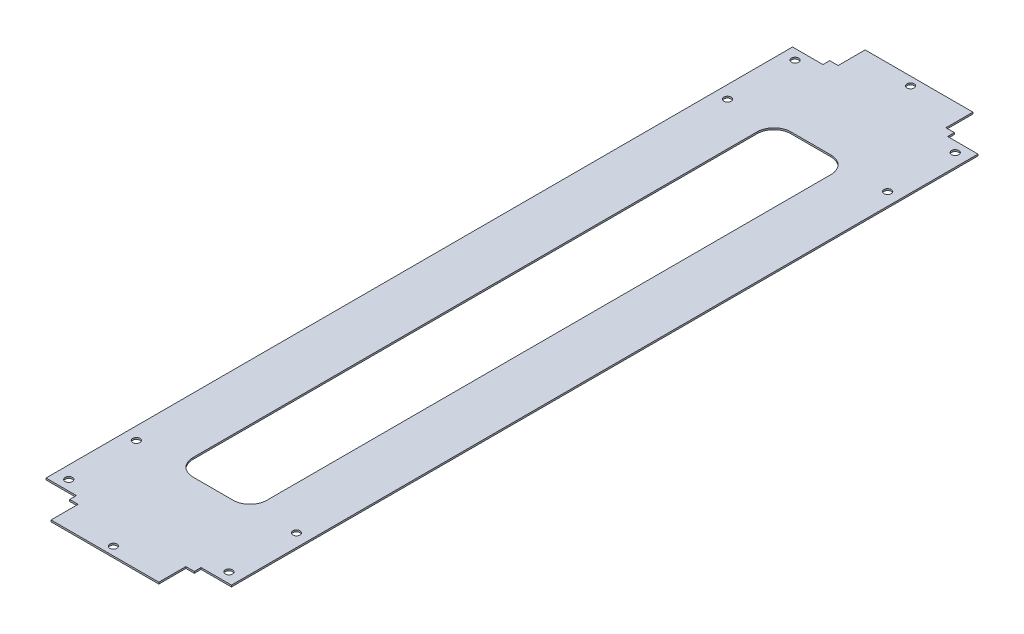
SolidWorks part; units mm, degrees
ref_plane "Front Plane" through (0, 0, 0) normal (0, 0, 1) x (1, 0, 0)
ref_plane "Top Plane" through (0, 0, 0) normal (0, 1, 0) x (1, 0, 0)
ref_plane "Right Plane" through (0, 0, 0) normal (1, 0, 0) x (0, 0, -1)
sketch "Sketch1" plane through (0, 0, 0) normal (0, 1, 0) x (1, 0, 0)
  line L0 (0, 0) -> (0, 221) construction
  line L1 (-54.9, -221) -> (-36.9, -221)
  line L3 (-36.9, 221) -> (-54.9, 221)
  line L4 (-54.9, 221) -> (-54.9, -221)
  line L16 (36.9, -221) -> (54.9, -221)
  line L17 (54.9, -221) -> (54.9, 221)
  line L25 (54.9, 221) -> (36.9, 221)
  line L26 (36.9, 221) -> (36.9, -221) construction
  line L27 (-21.9, 0) -> (0, 0) construction
  line L28 (-36.9, 221) -> (-36.9, 225)
  line L31 (-36.9, -221) -> (36.9, -221) construction
  line L32 (-36.9, 225) -> (-31.9, 225)
  line L33 (-31.9, 225) -> (-31.9, 241)
  line L35 (-36.9, 221) -> (36.9, 221) construction
  line L37 (-36.9, -221) -> (-36.9, 221) construction
  line L38 (0, 0) -> (21.9, 0) construction
  line L39 (-31.9, 241) -> (31.9, 241)
  line L40 (31.9, 241) -> (31.9, 225)
  line L41 (-21.9, 0) -> (-54.9, 0) construction
  line L42 (-21.9, 177) -> (21.9, 177)
  line L43 (-21.9, 177) -> (-21.9, -177)
  line L44 (-21.9, -177) -> (21.9, -177)
  line L45 (21.9, 177) -> (21.9, -177)
  line L46 (-21.9, 177) -> (21.9, -177) construction
  line L47 (-21.9, -177) -> (21.9, 177) construction
  line L48 (47.4, -175) -> (-47.4, -175) construction
  line L49 (47.4, -175) -> (47.4, 175) construction
  line L50 (47.4, 175) -> (-47.4, 175) construction
  line L51 (-47.4, -175) -> (-47.4, 175) construction
  line L52 (47.4, -175) -> (-47.4, 175) construction
  line L53 (47.4, 175) -> (-47.4, -175) construction
  line L54 (47.4, 215) -> (-47.4, 215) construction
  line L55 (47.4, 215) -> (47.4, -215) construction
  line L56 (47.4, -215) -> (-47.4, -215) construction
  line L57 (-47.4, 215) -> (-47.4, -215) construction
  line L58 (47.4, 215) -> (-47.4, -215) construction
  line L59 (47.4, -215) -> (-47.4, 215) construction
  line L60 (21.9, 0) -> (54.9, 0) construction
  line L61 (31.9, 225) -> (36.9, 225)
  line L62 (36.9, 225) -> (36.9, 221)
  line L63 (-31.9, 225) -> (31.9, 225) construction
  line L64 (0, 221) -> (0, 225) construction
  line L65 (-36.9, -221) -> (-36.9, -225)
  line L66 (-36.9, -225) -> (-31.9, -225)
  line L67 (-31.9, -225) -> (-31.9, -241)
  line L68 (-31.9, -241) -> (31.9, -241)
  line L69 (31.9, -241) -> (31.9, -225)
  line L70 (31.9, -225) -> (36.9, -225)
  line L71 (36.9, -225) -> (36.9, -221)
  line L72 (-31.9, -225) -> (31.9, -225) construction
  line L73 (0, -241) -> (0, -236) construction
  line L74 (0, 225) -> (0, 236) construction
  line L75 (0, 236) -> (0, 241) construction
  line L76 (0, -236) -> (0, -225) construction
  line L77 (0, -225) -> (0, -221) construction
  line L78 (0, -221) -> (0, 0) construction
  circle A2 centre (-47.4, 175) radius 2.15
  circle A3 centre (47.4, 175) radius 2.15
  circle A4 centre (-47.4, -175) radius 2.15
  circle A5 centre (47.4, -175) radius 2.15
  circle A6 centre (-47.4, -215) radius 2.15
  circle A7 centre (47.4, -215) radius 2.15
  circle A8 centre (47.4, 215) radius 2.15
  circle A9 centre (-47.4, 215) radius 2.15
  circle A10 centre (0, 236) radius 2.15
  circle A11 centre (0, -236) radius 2.15
  point P0 (0, 0)
  point P37 (0, 0)
  point P40 (0, 0)
  dimension "D12" = 4.3
  dimension "D5" = 40
  dimension "D15" = 94.8
  dimension "D3" = 10.5
  dimension "D14" = 10.5
  dimension "D4" = 18
  dimension "D16" = 18
  dimension "D18" = 4
  dimension "D11" = 38
  dimension "D7" = 10
  dimension "D6" = 21
  dimension "D9" = 4
  dimension "D19" = 63.8
  dimension "D20" = 5
  dimension "D8" = 73.8
  dimension "D13" = 430
  dimension "D17" = 450
  dimension "D21" = 442
  dimension "D10" = 15
extrude "Boss-Extrude1" add sketch "Sketch1" along normal blind 1
fillet "Fillet2" radius 10 4 edges at (21.9, 0.5, -177) (-21.9, 0.5, -177) (21.9, 0.5, 177) (-21.9, 0.5, 177)
equation "\"skin_sheetmetal_thickness\"= 0.80"
equation "\"base_width_skin_spacer\" = \"base_width_skin_target_width\" - 4 * \"skin_sheetmetal_thickness\" - 2 * \"base_width_skin_target_bend_radius\""
equation "\"base_width_skin_inner\" = \"base_width_skin_spacer\" + 2 * \"skin_sheetmetal_thickness\""
equation "\"base_width_skin_outer\" = \"base_width_skin_inner\" + 2 * \"skin_sheetmetal_thickness\""
equation "\"bend_cut_width\"= 3"
equation "\"bend_cut_length\"= 3"
equation "\"bend_offset_inner\"= 12.5"
equation "\"bend_offset_outer\" = \"bend_offset_inner\" + \"skin_sheetmetal_thickness\""
equation "\"border_offset_ends\"= 20"
equation "\"border_offset_sides\"= 10"
equation "\"border_offset_flange_horiz\"= 10"
equation "\"rivet_size\"= 4.3"
equation "\"rivet_offset_ends\"= \"rivet_spacing_horiz\"/2 - \"border_offset_ends\""
equation "\"rivet_spacing_horiz\"= 200"
equation "\"rivet_spacing_vert\"= 40"
equation "\"rivet_spacing_offset_right\"= 40"
equation "\"base_length\"= 200"
equation "\"D8@Sketch1\"=\"base_width_skin_spacer\""
equation "\"D19@Sketch1\"=\"base_width_skin_spacer\" - 10"
equation "\"D5@Sketch1\"=\"rivet_spacing_vert\""
equation "\"base_width_skin_spacer_length\" = 430"
equation "\"D13@Sketch1\"=\"base_width_skin_spacer_length\""
equation "\"bend_offset_spacer_tab\"= 21.0"
equation "\"D6@Sketch1\"=\"bend_offset_spacer_tab\""
equation "\"base_width_skin_target_width\" = 80"
equation "\"base_width_skin_target_bend_radius\" = 1.5"
